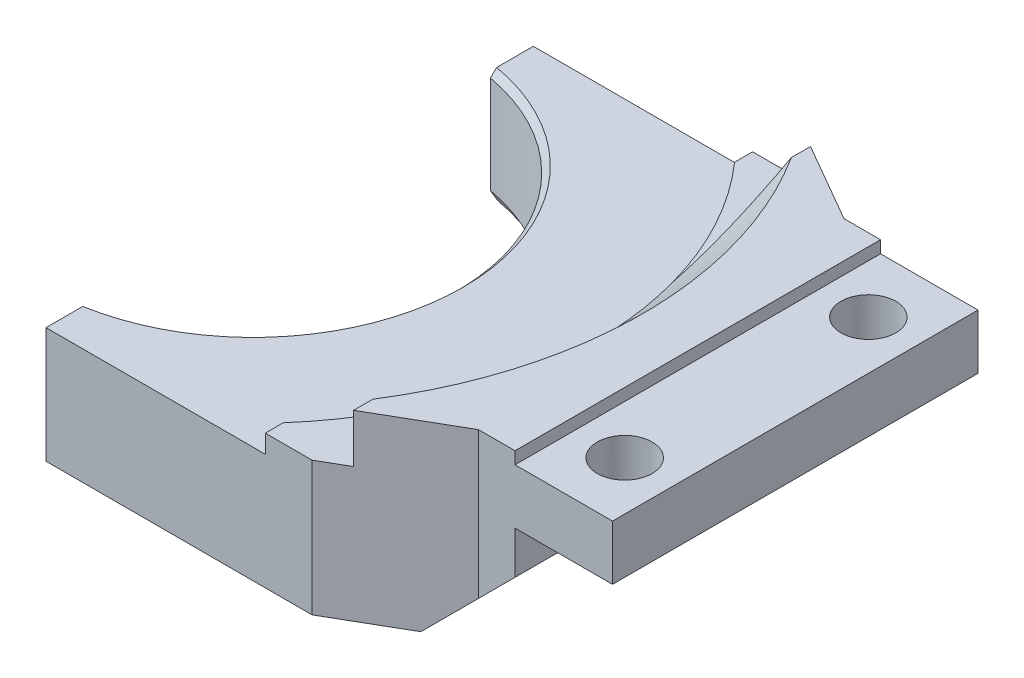
SolidWorks part; units mm, degrees
ref_plane "Alzado" through (0, 0, 0) normal (0, 0, 1) x (1, 0, 0)
ref_plane "Planta" through (0, 0, 0) normal (0, 1, 0) x (1, 0, 0)
ref_plane "Vista lateral" through (0, 0, 0) normal (1, 0, 0) x (0, 0, -1)
sketch "Croquis1" plane through (0, 0, 0) normal (0, 1, 0) x (1, 0, 0)
  line L0 (3, 20) -> (24.8397, 20)
  line L1 (24.8397, 20) -> (33.5, 15)
  line L2 (33.5, 15) -> (44.5, 15)
  line L3 (44.5, 15) -> (44.5, -15)
  line L4 (44.5, -15) -> (33.5, -15)
  line L5 (33.5, -15) -> (24.8397, -20)
  line L6 (24.8397, -20) -> (3, -20)
  line L7 (3, -20) -> (3, -16.4792)
  line L8 (3, 16.4792) -> (3, 20)
  arc A0 (3, -16.4792) -> (3, 16.4792) centre (0, 0) ccw
  circle A1 centre (40.5, 10) radius 2.25
  circle A2 centre (40.5, -10) radius 2.25
  dimension "D11" = 16.75
  dimension "D12" = 4
  dimension "D13" = 4
  dimension "D14" = 10
  dimension "D16" = 4.5
  dimension "D17" = 4.5
  dimension "D1" = 41.5
  dimension "D2" = 20
  dimension "D3" = 20
  dimension "D4" = 15
  dimension "D5" = 15
  dimension "D6" = 11
  dimension "D7" = 11
  dimension "D8" = 30
  dimension "D9" = 30
  dimension "D10" = 3
  dimension "D15" = 10
extrude "Saliente-Extruir2" add sketch "Croquis1" along normal blind 15 contours A0 L8 L0 L1 L2 L3 L4 L5 L6 L7
sketch "Croquis2" plane through (0, 15, 0) normal (0, 1, 0) x (1, 0, 0)
  line L0 (33.5, -15) -> (44.5, -15) construction
  line L1 (44.5, 15) -> (36.5, 15)
  line L2 (44.5, 15) -> (44.5, -15)
  line L3 (44.5, -15) -> (36.5, -15)
  line L4 (36.5, 15) -> (36.5, -15)
  dimension "D1" = 8
extrude "Cortar-Extruir1" cut sketch "Croquis2" against normal blind 1
sketch "Croquis3" plane through (0, 0, 0) normal (0, 0, 1) x (1, 0, 0)
  line L0 (16.75, 0) -> (16.75, 1)
  line L1 (3, 0) -> (16.75, 0) construction
  line L2 (16.75, 1) -> (17.3274, 0)
  line L3 (24.8397, 0) -> (3, 0) construction
  line L4 (17.3274, 0) -> (16.75, 0)
  dimension "D1" = 1
  dimension "D2" = 30
  dimension "D3" = 16.75
revolve "Cortar-Revolución1" cut sketch "Croquis3" angle 360 about axis through (0, 15, 0) along (0, -1, 0)
sketch "Croquis5" plane through (0, 15, 0) normal (0, 1, 0) x (1, 0, 0)
  circle A0 centre (0, 0) radius 28
  dimension "D1" = 56
extrude "Cortar-Extruir2" cut sketch "Croquis5" against normal blind 5.5
chamfer "Chaflán1" distance 4 angle 45 1 edges at (28, 15, 0)
sketch "Croquis6" plane through (0, 0, 20) normal (0, 0, 1) x (1, 0, 0)
  line L0 (0, 15) -> (27, 15)
  line L1 (27, 15) -> (27, 11)
  line L2 (27, 11) -> (0, 11)
  line L3 (0, 11) -> (0, 15)
  line L4 (3, 0) -> (24.8397, 0) construction
  dimension "D1" = 27
  dimension "D2" = 4
  dimension "D3" = 15
extrude "Cortar-Extruir3" cut sketch "Croquis6" against normal through all
sketch "Croquis7" plane through (0, 0, 20) normal (0, 0, 1) x (1, 0, 0)
  line L0 (21, 11) -> (0, 11)
  line L1 (19.5959, 11) -> (24.8397, 11) construction
  line L2 (0, 11) -> (0, 9.5)
  line L3 (0, 9.5) -> (21, 9.5)
  line L4 (21, 9.5) -> (21, 11)
  dimension "D1" = 21
  dimension "D2" = 1.5
extrude "Cortar-Extruir4" cut sketch "Croquis7" against normal through all
sketch "Croquis8" plane through (0, 0, 15) normal (0, 0, 1) x (1, 0, 0)
  line L1 (44.5, 0) -> (36.5, 0)
  line L2 (44.5, 0) -> (44.5, 9.5)
  line L3 (44.5, 9.5) -> (36.5, 9.5)
  line L4 (36.5, 0) -> (36.5, 9.5)
  dimension "D1" = 36.5
  dimension "D2" = 9.5
extrude "Cortar-Extruir5" cut sketch "Croquis8" against normal up to next
chamfer "Chaflán2" distance 6 angle 45 1 edges at (36.5, 0, 0)
chamfer "Chaflán3" distance 0.5 angle 45 1 edges at (16.75, 9.5, 0)
sketch "Croquis9" plane through (36.5, 0, 0) normal (1, 0, 0) x (0, 0, -1)
  circle A0 centre (0, 5) radius 3.5
  dimension "D1" = 7
  dimension "D2" = 5
extrude "Cortar-Extruir6" cut sketch "Croquis9" against normal through all
sketch "Croquis10" plane through (36.5, 0, 0) normal (1, 0, 0) x (0, 0, -1)
  circle A0 centre (0, 5) radius 4
  dimension "D1" = 8
extrude "Cortar-Extruir7" cut sketch "Croquis10" against normal blind 19.5
